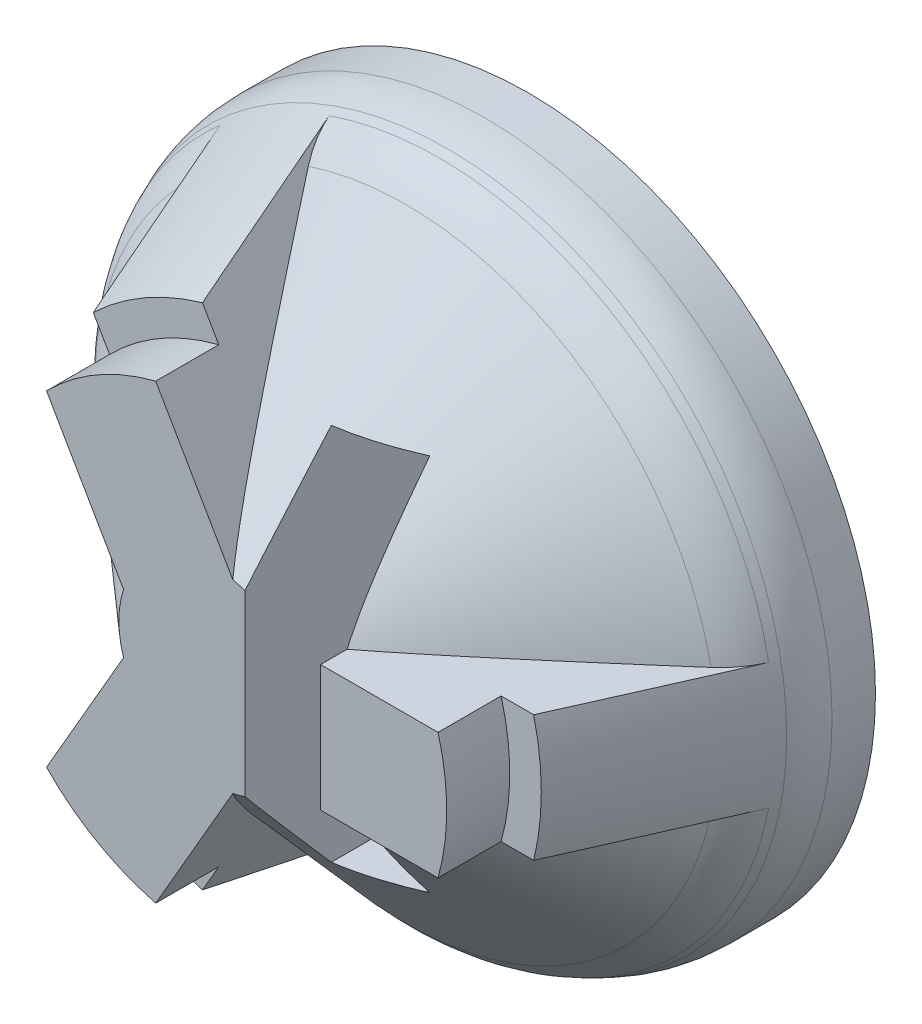
SolidWorks part; units mm, degrees
ref_plane "Plan de face" through (0, 0, 0) normal (0, 0, 1) x (1, 0, 0)
ref_plane "Plan de dessus" through (0, 0, 0) normal (0, 1, 0) x (1, 0, 0)
ref_plane "Plan de droite" through (0, 0, 0) normal (1, 0, 0) x (0, 0, -1)
sketch "Esquisse1" plane through (0, 0, 0) normal (0, 0, 1) x (1, 0, 0)
  line L0 (0, 0) -> (12, 0) construction
  line L1 (0, 0) -> (-6, 10.3923) construction
  line L2 (0, 0) -> (-6, -10.3923) construction
  line L3 (11.8322, 2) -> (2.2361, 2)
  line L4 (11.8322, -2) -> (2.2361, -2)
  line L5 (-4.184, -11.247) -> (0.614, -2.9365)
  line L6 (-7.6481, -9.247) -> (-2.8501, -0.9365)
  line L7 (-7.6481, 9.247) -> (-2.8501, 0.9365)
  line L8 (-4.184, 11.247) -> (0.614, 2.9365)
  circle A0 centre (0, 0) radius 12 construction
  circle A1 centre (0, 0) radius 3 construction
  circle A2 centre (0, 0) radius 3 construction
  arc A3 (11.8322, 2) -> (11.8322, -2) centre (0, 0) cw
  arc A4 (2.2361, -2) -> (1.5, -2.5981) centre (0, 0) cw
  arc A5 (2.2361, 2) -> (1.5, 2.5981) centre (0, 0) ccw
  arc A6 (0.614, -2.9365) -> (1.5, -2.5981) centre (0, 0) ccw
  arc A7 (-4.184, -11.247) -> (-7.6481, -9.247) centre (0, 0) cw
  arc A8 (-2.8501, -0.9365) -> (-3, 0) centre (0, 0) cw
  arc A9 (-2.8501, 0.9365) -> (-3, 0) centre (0, 0) ccw
  arc A10 (-7.6481, 9.247) -> (-4.184, 11.247) centre (0, 0) cw
  arc A11 (0.614, 2.9365) -> (1.5, 2.5981) centre (0, 0) cw
  point P30 (0, 0)
  dimension "D1" = 24
  dimension "D2" = 6
  dimension "D3" = 6
  dimension "D4" = 120
  dimension "D5" = 4
  dimension "D6" = 3
extrude "Boss.-Extru.1" add sketch "Esquisse1" along normal blind 10 contours A11 L8 A10 L7 A9 A8 L6 A7 L5 A6 A4 L4 A3 L3 A5
sketch "Esquisse4" plane through (0, 0, 0) normal (0, 1, 0) x (1, 0, 0)
  line L0 (12, 0) -> (3, -10) construction
  line L1 (3, -10) -> (0, -10)
  line L2 (0.614, -10) -> (2.2361, -10) construction
  line L3 (0, -10) -> (0, 0)
  line L4 (0, 0) -> (12, 0) construction
  line L5 (12, 0) -> (11.8322, 0) construction
  line L6 (11.8322, -10) -> (2.2361, -10) construction
  line L9 (12, -10) -> (12, 0) construction
  line L10 (12, -2) -> (12, 0)
  line L11 (12, 0) -> (0, 0)
  line L12 (3, -10) -> (12, -2)
  dimension "D1" = 2
  dimension "3" = 3
revolve "Révolution1" add sketch "Esquisse4" angle 360 about L3
sketch "Esquisse5" plane through (0, 0, 0) normal (0, 0, -1) x (-1, 0, 0)
  circle A0 centre (0, 0) radius 10.2
  dimension "D1" = 20.4
extrude "Enlèv. mat.-Extru.1" cut sketch "Esquisse5" against normal blind 1
sketch "Esquisse6" plane through (0, 0, 0) normal (0, 1, 0) x (1, 0, 0)
  line L0 (11, 0) -> (15.4808, 0)
  line L1 (11, 0) -> (11, -2)
  line L2 (15.4808, 0) -> (15.4808, -10)
  line L3 (15.4808, -10) -> (7.75, -10)
  line L4 (7.75, -10) -> (11, 0) construction
  line L5 (11.8322, -2) -> (-4.184, -2) construction
  line L6 (0, 0) -> (0, -11.8612) construction
  line L7 (11, -2) -> (8.4, -8)
  line L8 (11.8322, -10) -> (2.2361, -10) construction
  line L9 (11.8322, -10) -> (2.2361, -10) construction
  line L11 (8.4, -8) -> (7.4, -8)
  line L12 (7.4, -8) -> (7.4, -10)
  line L13 (7.4, -10) -> (7.75, -10)
  line L14 (12, -10) -> (12, 0) construction
  line L15 (12, 0) -> (-12, 0) construction
  dimension "D1" = 1
  dimension "D2" = 1
  dimension "D3" = 2
  dimension "D4" = 7.4
revolve "Enlèvement de matière-Révolution1" cut sketch "Esquisse6" angle 360 about L6
fillet "Congé2" radius 3 4 edges at (5.1867, -8.9837, 3.4458) (-10.3735, 0, 3.4458) (5.1867, 8.9837, 3.4458) (-11, 0, 2)
sketch "Esquisse7" plane through (0, 0, 10) normal (0, 0, 1) x (1, 0, 0)
  line L0 (1, 6) -> (3.4, 6)
  line L1 (3.4, 6) -> (3.4, -6)
  line L2 (3.4, -6) -> (1, -6)
  line L3 (1, -6) -> (1, 6)
  line L4 (0, 0) -> (7.4, 0) construction
  arc A2 (7.1246, -2) -> (7.1246, 2) centre (0, 0) ccw construction
  dimension "D1" = 12
  dimension "D2" = 12
  dimension "D3" = 2.4
  dimension "D4" = 1
extrude "Enlèv. mat.-Extru.2" cut sketch "Esquisse7" against normal offset from surface (8 mm away) 1 up to face at (-10.2, 0, 1)
